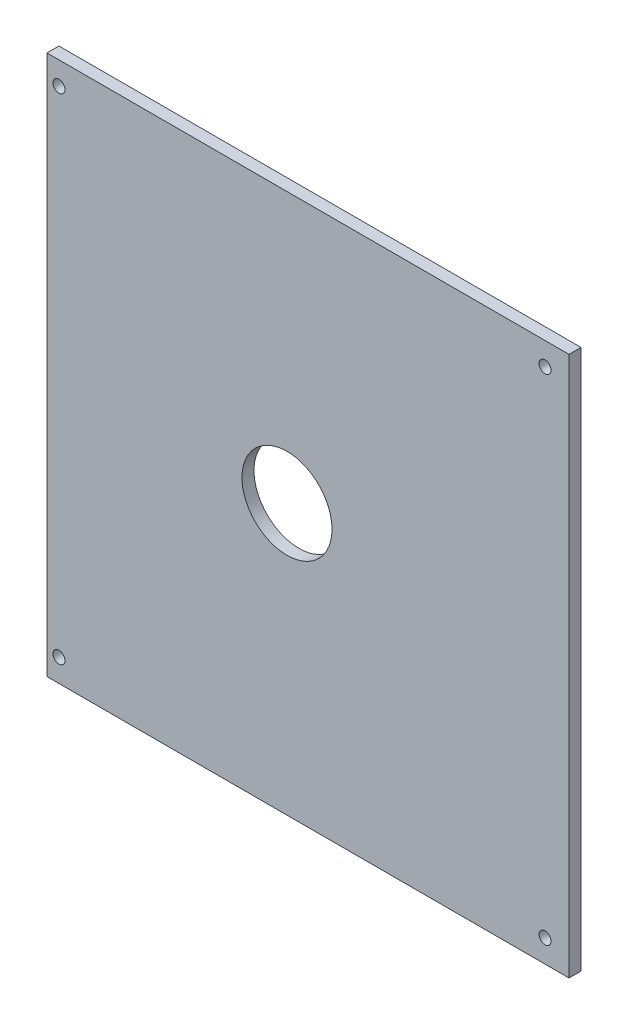
SolidWorks part; units mm, degrees
ref_plane "Front Plane" through (0, 0, 0) normal (0, 0, 1) x (1, 0, 0)
ref_plane "Top Plane" through (0, 0, 0) normal (0, 1, 0) x (1, 0, 0)
ref_plane "Right Plane" through (0, 0, 0) normal (1, 0, 0) x (0, 0, -1)
sketch "Sketch1" plane through (0, 0, 0) normal (0, 0, 1) x (1, 0, 0)
  line L5 (0, 0) -> (110.49, 0)
  line L6 (0, 0) -> (0, -114.3)
  line L7 (0, -114.3) -> (110.49, -114.3)
  line L8 (110.49, 0) -> (110.49, -114.3)
  dimension "D1" = 110.49
  dimension "D2" = 114.3
extrude "Boss-Extrude1" add sketch "Sketch1" along normal blind 2.54
sketch "Sketch2" plane through (0, 0, 2.54) normal (0, 0, 1) x (1, 0, 0)
  line L3 (0, 0) -> (0, -114.3) construction
  line L4 (110.49, 0) -> (0, 0) construction
  circle A0 centre (50.8, -57.15) radius 9.525
  dimension "D1" = 19.05
  dimension "D2" = 50.8
  dimension "D6" = 57.15
extrude "Cut-Extrude1" cut sketch "Sketch2" against normal blind 2.54
sketch "Sketch3" plane through (0, 0, 2.54) normal (0, 0, 1) x (1, 0, 0)
  line L0 (55.245, 0) -> (55.245, -10.1816) construction
  line L1 (0, 0) -> (110.49, 0) construction
  line L2 (0, -57.15) -> (13.4518, -57.15) construction
  line L4 (0, 0) -> (0, -114.3) construction
  line L5 (0, -114.3) -> (110.49, -114.3) construction
  line L6 (110.49, 0) -> (0, 0) construction
  line L7 (110.49, -114.3) -> (110.49, 0) construction
  circle A0 centre (2.54, -4.826) radius 1.27
  circle A5 centre (2.54, -109.474) radius 1.27
  circle A6 centre (105.41, -4.826) radius 1.27
  circle A7 centre (105.41, -109.474) radius 1.27
  dimension "D1" = 2.54
  dimension "D2" = 4.826
  dimension "D3" = 2.54
  dimension "D4" = 2.54
  dimension "D5" = 2.54
  dimension "D6" = 4.826
  dimension "D7" = 4.826
  dimension "D8" = 5.08
  dimension "D9" = 5.08
extrude "Cut-Extrude2" cut sketch "Sketch3" against normal through all
